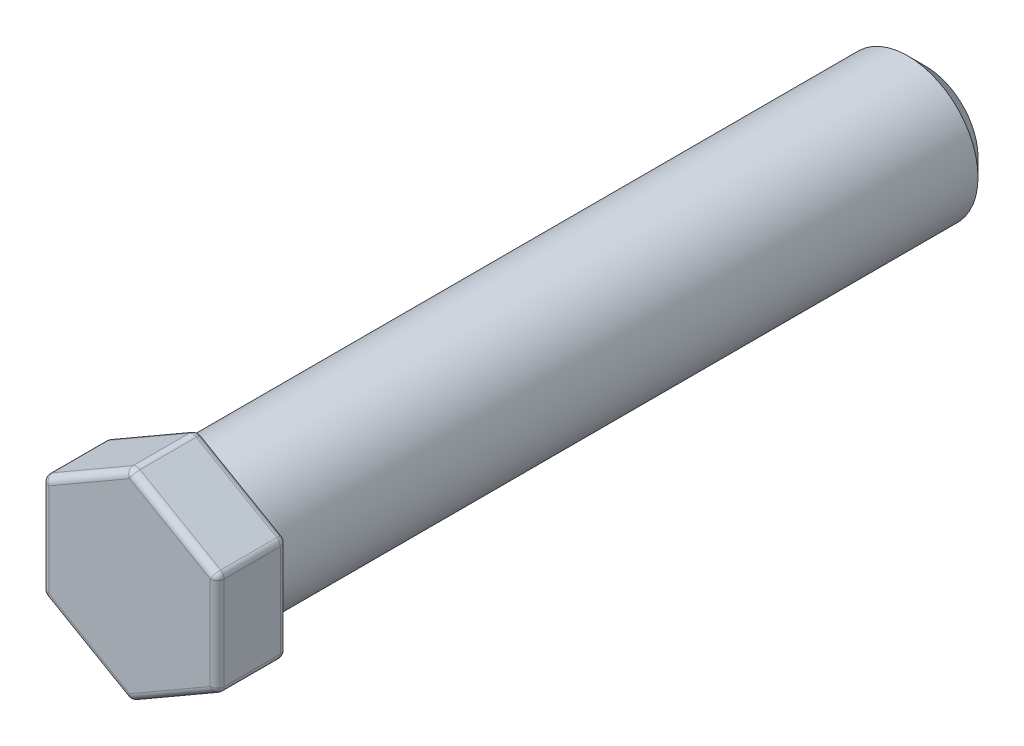
SolidWorks part; units mm, degrees
ref_plane "Front Plane" through (0, 0, 0) normal (0, 0, 1) x (1, 0, 0)
ref_plane "Top Plane" through (0, 0, 0) normal (0, 1, 0) x (1, 0, 0)
ref_plane "Right Plane" through (0, 0, 0) normal (1, 0, 0) x (0, 0, -1)
sketch "Sketch1" plane through (0, 0, 0) normal (0, 0, 1) x (1, 0, 0)
  circle A0 centre (0, 0) radius 2
  dimension "D1" = 4
extrude "Boss-Extrude1" add sketch "Sketch1" along normal blind 20.7
sketch "Sketch2" plane through (0, 0, 20.7) normal (0, 0, 1) x (1, 0, 0)
  line L1 (2.5, -1.4434) -> (2.5, 1.4434)
  line L2 (2.5, 1.4434) -> (0, 2.8868)
  line L3 (0, 2.8868) -> (-2.5, 1.4434)
  line L4 (-2.5, 1.4434) -> (-2.5, -1.4434)
  line L5 (-2.5, -1.4434) -> (0, -2.8868)
  line L6 (0, -2.8868) -> (2.5, -1.4434)
  circle A0 centre (0, 0) radius 2.5 construction
  dimension "D1" = 5
extrude "Boss-Extrude2" add sketch "Sketch2" along normal blind 2
fillet "Fillet1" radius 0.2 13 edges at (-1.25, -2.1651, 22.7) (-2.5, 0, 22.7) (-1.25, 2.1651, 22.7) (1.25, 2.1651, 22.7) (2.5, 0, 22.7) (1.25, -2.1651, 22.7) (2.5, 0, 20.7) (1.25, 2.1651, 20.7) (-1.25, 2.1651, 20.7) (-2.5, 0, 20.7) (-1.25, -2.1651, 20.7) (1.25, -2.1651, 20.7) (2, 0, 20.7)
fillet "Fillet2" radius 0.2 18 edges at (0, -2.8191, 22.6414) (0, -2.8191, 20.7586) (-2.4414, -1.4096, 22.6414) (-2.4414, -1.4096, 20.7586) (-2.4414, 1.4096, 22.6414) (-2.4414, 1.4096, 20.7586) (2.4414, 1.4096, 22.6414) (2.4414, 1.4096, 20.7586) (2.4414, -1.4096, 22.6414) (2.4414, -1.4096, 20.7586) (0, 2.8191, 22.6414) (0, 2.8191, 20.7586) (0, -2.8868, 21.7) (-2.5, -1.4434, 21.7) (-2.5, 1.4434, 21.7) (2.5, 1.4434, 21.7) (2.5, -1.4434, 21.7) (0, 2.8868, 21.7)
chamfer "Chamfer1" distance 0.5 angle 45 1 edges at (2, 0, 0)
